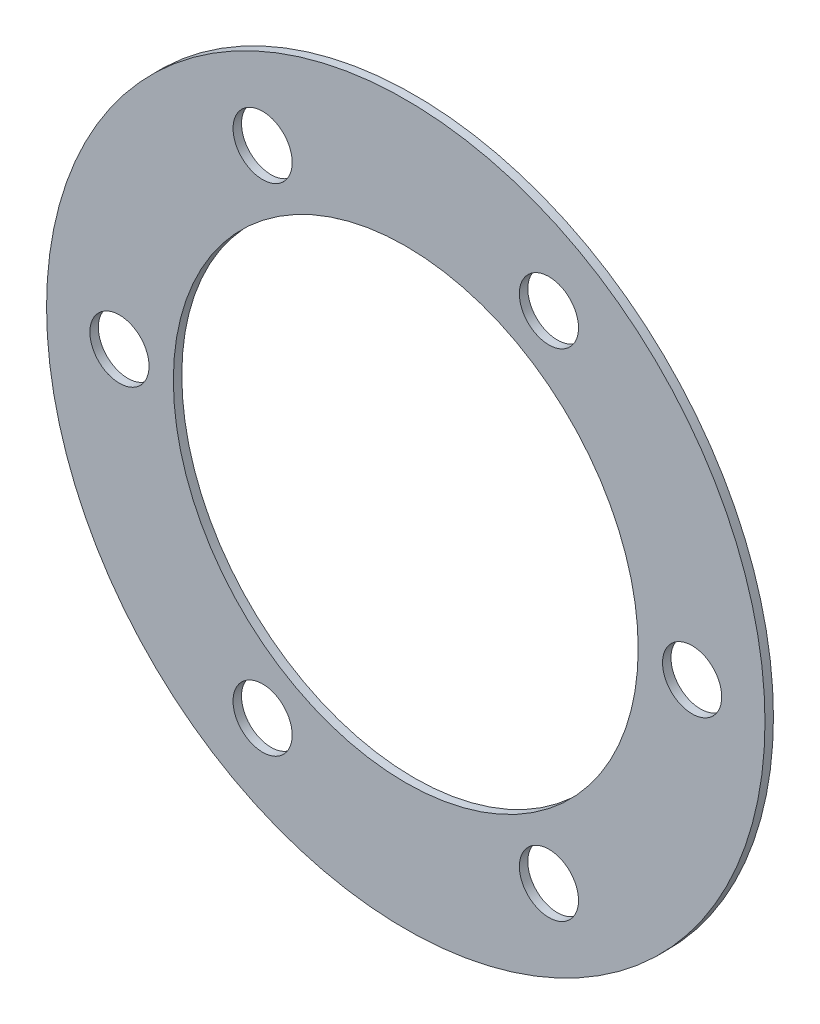
SolidWorks part; units mm, degrees
ref_plane "Front Plane" through (0, 0, 0) normal (0, 0, 1) x (1, 0, 0)
ref_plane "Top Plane" through (0, 0, 0) normal (0, 1, 0) x (1, 0, 0)
ref_plane "Right Plane" through (0, 0, 0) normal (1, 0, 0) x (0, 0, -1)
sketch "Sketch1" plane through (0, 0, 0) normal (0, 0, 1) x (1, 0, 0)
  circle A0 centre (0, 0) radius 42.5
  circle A1 centre (0, 0) radius 27.5
  dimension "D1" = 85
  dimension "D2" = 55
extrude "Boss-Extrude1" add sketch "Sketch1" along normal blind 1
hole_wizard "M6 Clearance Hole1" positions "Sketch4" profile "Sketch5" hole size "M6" standard "ISO" end condition through all
sketch "Sketch4" plane through (0, 0, 1) normal (0, 0, 1) x (1, 0, 0)
  point P0 (-33.875, 0)
  point P3 (-16.9375, -29.3366)
  point P6 (16.9375, -29.3366)
  point P9 (33.875, 0)
  point P12 (16.9375, 29.3366)
  point P15 (-16.9375, 29.3366)
sketch "Sketch5" plane through (-33.875, 0, 1) normal (1, 0, 0) x (0, -1, 0)
  line L0 (0, 0) -> (0, 1)
  line L1 (0, 1) -> (3.5, 1)
  line L2 (3.5, 1) -> (3.5, 0)
  line L5 (3.5, 0) -> (0, 0)
  line L11 (0, -6.35) -> (0, 107.95) construction
  dimension "Thru Hole Dia." = 7
  dimension "Thru Hole Depth" = 1
